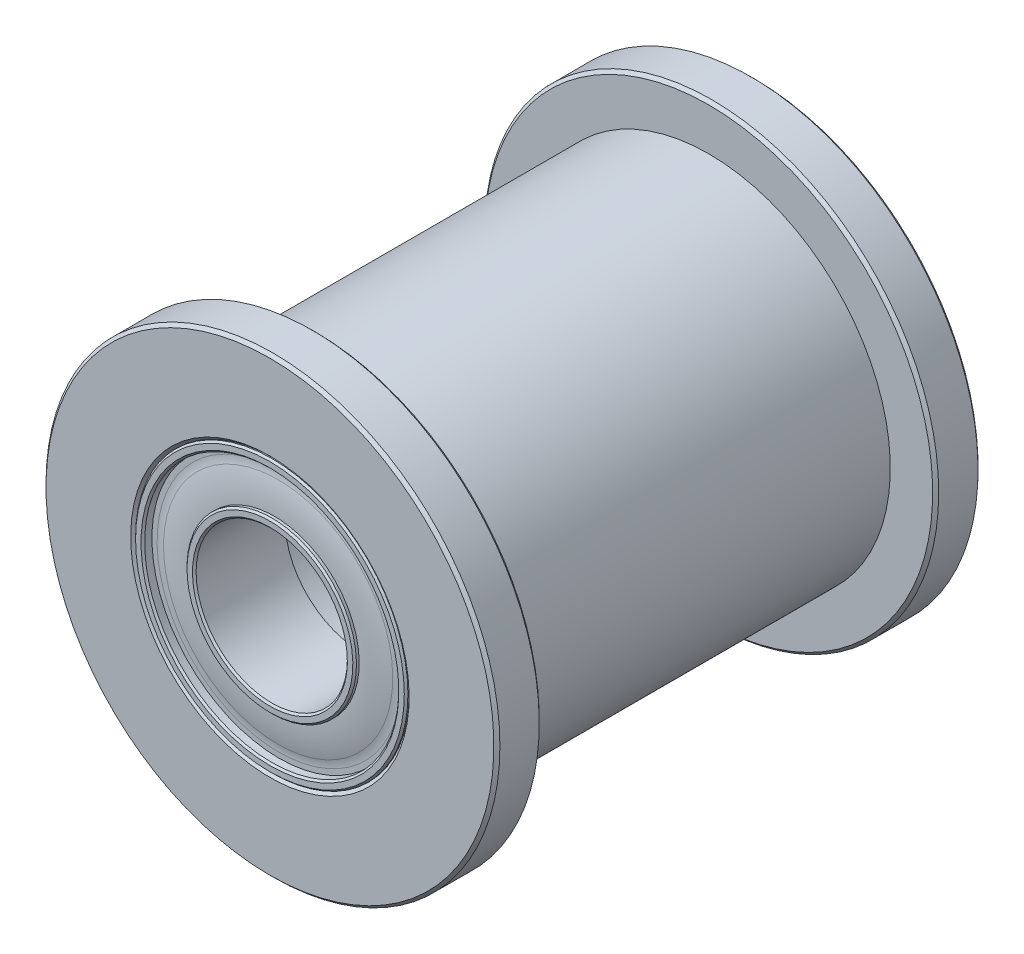
SolidWorks part; units mm, degrees
ref_plane "Front" through (0, 0, 0) normal (0, 0, 1) x (1, 0, 0)
ref_plane "Top" through (0, 0, 0) normal (0, 1, 0) x (1, 0, 0)
ref_plane "Right" through (0, 0, 0) normal (1, 0, 0) x (0, 0, -1)
sketch "Sketch1" plane through (0, 0, 0) normal (1, 0, 0) x (0, 0, -1)
  line L0 (-8, 0) -> (8, 0) construction
  line L1 (8, 7.5) -> (8, -7.5) construction
  line L2 (8, 7.5) -> (6.5, 7.5) construction
  line L3 (8, 2.5) -> (8, -2.5) construction
  line L4 (8, 6) -> (8, -6) construction
  line L5 (6, 0) -> (-6, 0) construction
  line L6 (6.5, 7.5) -> (6.5, 6) construction
  line L7 (8, 4.5) -> (5, 4.5) construction
  line L8 (5, 4.5) -> (5, 2.5) construction
  line L9 (5, 2.5) -> (8, 2.5) construction
  line L10 (8, 4.5) -> (8, -4.5) construction
  line L11 (-8, 0) -> (-8, 7.5) construction
  line L12 (-8, 7.5) -> (-6.5, 7.5) construction
  line L13 (-6.5, 7.5) -> (-6.5, 6) construction
  line L14 (-6.5, 6) -> (6.5, 6) construction
  line L15 (6.5, 6) -> (6.5, -6) construction
  line L16 (6.5, -6) -> (-6.5, -6) construction
  line L17 (-6.5, -6) -> (-6.5, 6) construction
  line L18 (0, -3.5) -> (0, 3.5) construction
  point P15 (8, 0)
  point P22 (6.5, 0)
  point P24 (-6, -6)
  point P25 (6, -6)
  point P29 (0, 0)
  dimension "Width" = 16
  dimension "OD" = 15
  dimension "ID" = 5
  dimension "Diameter" = 12
  dimension "Groove Depth" = 1.5
  dimension "For Maximum Belt Width" = 12
  dimension "For Shaft Diameter" = 5
  dimension "Bearing Diameter" = 9
  dimension "Bearing Width" = 3
  dimension "Inside Width" = 13
  dimension "Wall Thickness" = 1.5
  dimension "D1" = 7
sketch "Sketch5" plane through (0, 0, 0) normal (0, 0, 1) x (1, 0, 0)
  circle A0 centre (0, 0) radius 7.5 construction
  circle A1 centre (0, 0) radius 6 construction
  circle A2 centre (0, 0) radius 2.5 construction
  point P5 (0, 0)
  point P9 (-6, 0)
  point P10 (-7.5, 0)
  point P13 (0, 6)
sketch "Sketch2" plane through (0, 0, 0) normal (1, 0, 0) x (0, 0, -1)
  line L0 (8, 2.5) -> (5, 2.5)
  line L1 (8, 2.5) -> (8, 2.8)
  line L2 (8, 7.5) -> (8, -7.5) construction
  line L3 (8, 2.8) -> (7.7, 2.8) construction
  line L4 (7.85, 4.2) -> (7.85, 2.8) construction
  line L5 (8, 4.5) -> (5, 4.5)
  line L6 (7.7, 3.9) -> (7.7, 4.2)
  line L7 (8, 4.5) -> (8, 4.2)
  line L8 (8, 4.2) -> (7.7, 4.2)
  line L9 (7.7, 4.2) -> (7.7, 2.8) construction
  line L10 (5, 4.5) -> (5, 2.5)
  line L11 (7.85, 2.8) -> (8, 2.8)
  arc A0 (7.7, 3.9) -> (7.85, 2.8) centre (3.7417, 2.8) cw
  dimension "D1" = 0.3
revolve "Revolve1" add sketch "Sketch2" angle 360 about L0
chamfer "Chamfer2" distance 0.06 angle 45 4 edges at (0, -2.8, -8) (0, -2.5, -8) (0, -4.2, -8) (0, -4.5, -8)
fillet "Fillet2" radius 1 1 edges at (0, -3.9, -7.7)
mirror "Mirror1" about plane through (0, 0, 0) normal (0, 0, 1) of bodies 108
sketch "Sketch3" plane through (0, 0, 0) normal (1, 0, 0) x (0, 0, -1)
  line L0 (6.5, 7.5) -> (8, 7.5)
  line L1 (8, 7.5) -> (8, 4.5)
  line L2 (8, 7.5) -> (8, -7.5) construction
  line L3 (-8, 4.5) -> (-5, 4.5)
  line L4 (-5, 4.5) -> (-5, 3.5)
  line L5 (-5, 3.5) -> (5, 3.5)
  line L6 (5, 3.5) -> (5, 4.5)
  line L8 (5, 4.5) -> (8, 4.5)
  line L9 (6.5, 7.5) -> (6.5, 6)
  line L10 (6.5, 6) -> (-6.5, 6)
  line L11 (0, 6) -> (0, 4.5) construction
  line L12 (-8, 4.5) -> (8, 4.5) construction
  line L13 (-6.5, 7.5) -> (-6.5, 6)
  line L19 (-8, 7.5) -> (-8, 4.5)
  line L20 (-6.5, 7.5) -> (-8, 7.5)
revolve "Revolve2" add sketch "Sketch3" angle 360 about L0
chamfer "Chamfer1" distance 0.1 angle 45 6 edges at (0, -7.5, -8) (0, -7.5, -6.5) (0, -7.5, 6.5) (0, -7.5, 8) (0, -4.5, -8) (0, -4.5, 8)
equation "\"D1@Sketch1\"=\"ID@Sketch1\"+2"
